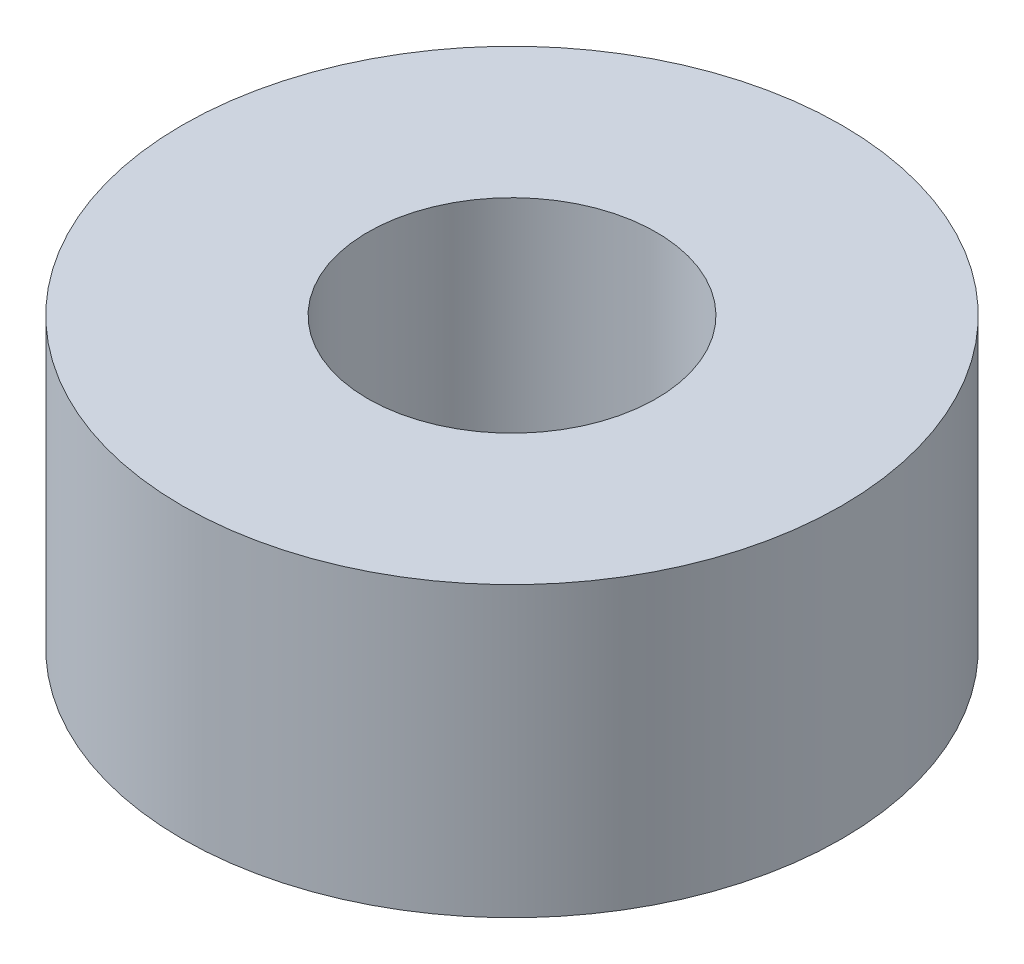
SolidWorks part; units mm, degrees
ref_plane "Front" through (0, 0, 0) normal (0, 0, 1) x (1, 0, 0)
ref_plane "Top" through (0, 0, 0) normal (0, 1, 0) x (1, 0, 0)
ref_plane "Right" through (0, 0, 0) normal (1, 0, 0) x (0, 0, -1)
sketch "Sketch1" plane through (0, 0, 0) normal (0, 1, 0) x (1, 0, 0)
  circle A0 centre (0, 0) radius 4
  circle A1 centre (0, 0) radius 1.75
  dimension "D1" = 8
  dimension "D2" = 3.5
extrude "Boss-Extrude1" add sketch "Sketch1" along normal blind 3.5 contours A0 A1
